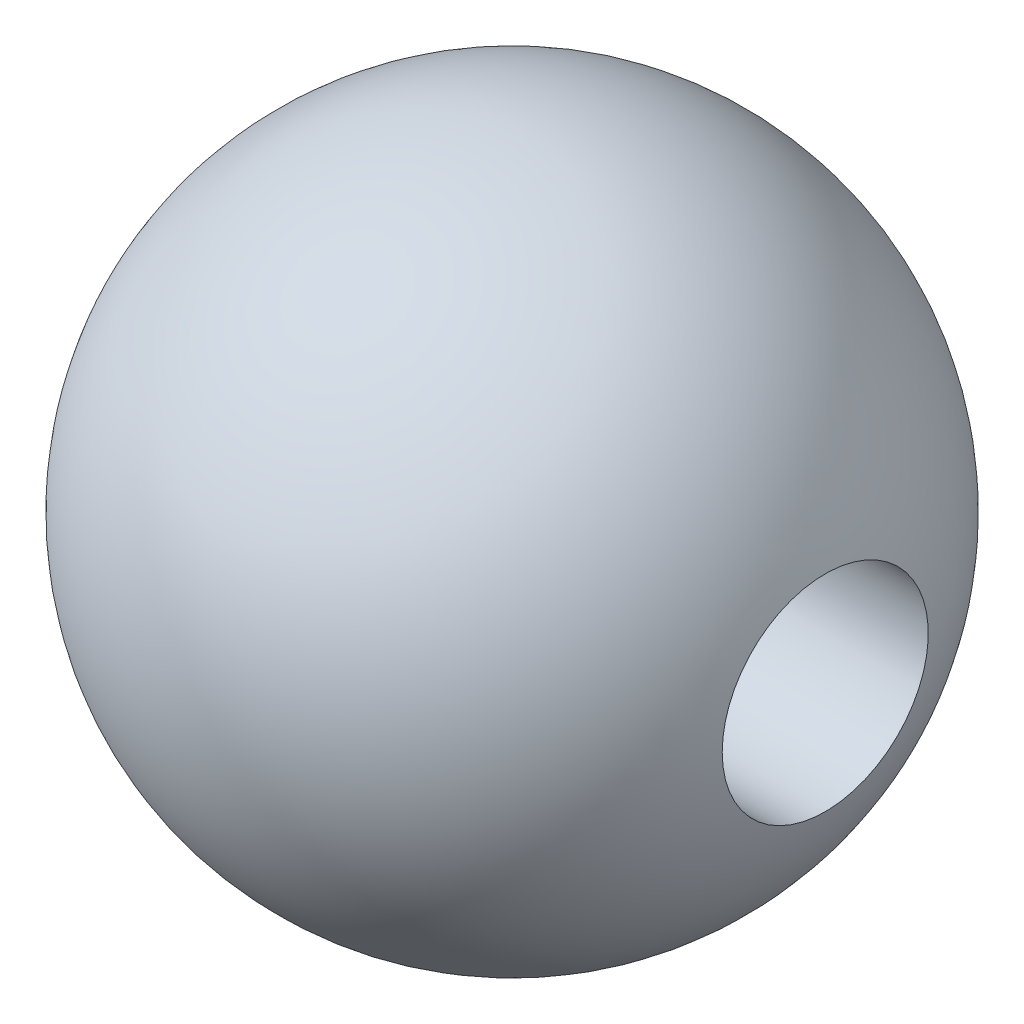
SolidWorks part; units mm, degrees
ref_plane "前视基准面" through (0, 0, 0) normal (0, 0, 1) x (1, 0, 0)
ref_plane "上视基准面" through (0, 0, 0) normal (0, 1, 0) x (1, 0, 0)
ref_plane "右视基准面" through (0, 0, 0) normal (1, 0, 0) x (0, 0, -1)
sketch "Sketch1" plane through (0, 0, 0) normal (0, 1, 0) x (1, 0, 0)
  line L0 (0, 0) -> (3.5535, 1.8365) construction
  circle A0 centre (0, 0) radius 8
revolve "Revolve2" add sketch "Sketch1" angle 360 about L0
ref_plane "Plane1" through (8, 0, 0) normal (1, 0, 0) x (0, 0, -1)
sketch "Sketch2" plane through (8, 0, 0) normal (1, 0, 0) x (0, 0, -1)
  circle A0 centre (0, 0) radius 2.5
extrude "Cut-Extrude1" cut sketch "Sketch2" against normal blind 20
